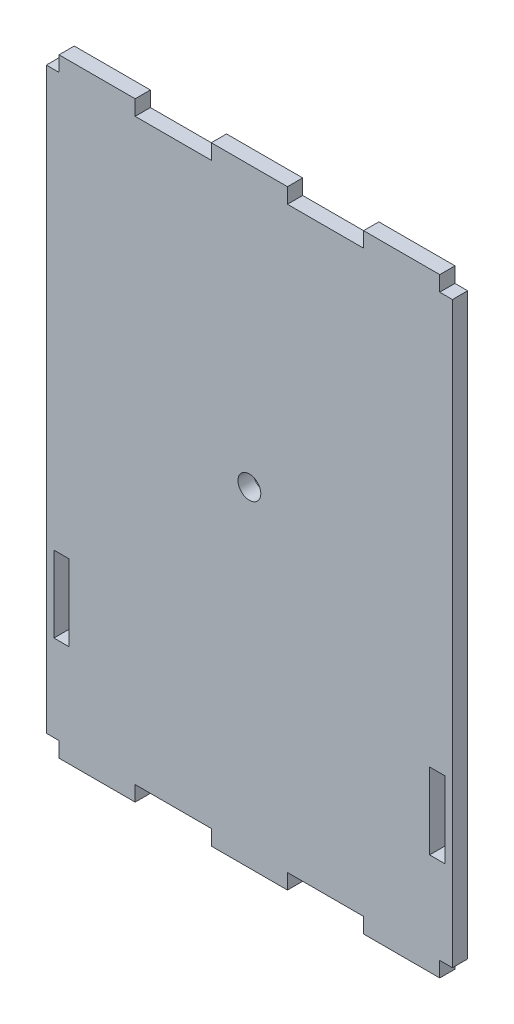
SolidWorks part; units mm, degrees
ref_plane "前视基准面" through (0, 0, 0) normal (0, 0, 1) x (1, 0, 0)
ref_plane "上视基准面" through (0, 0, 0) normal (0, 1, 0) x (1, 0, 0)
ref_plane "右视基准面" through (0, 0, 0) normal (1, 0, 0) x (0, 0, -1)
other "Configuration Table"
sketch "草图1" plane through (0, 0, 0) normal (0, 0, 1) x (1, 0, 0)
  line L0 (2.5, 3) -> (0, 3)
  line L2 (0, 3) -> (0, 117)
  line L4 (80, 3) -> (80, 117)
  line L5 (2.5, 0) -> (17.5, 0)
  line L6 (2.5, 0) -> (2.5, 3)
  line L8 (17.5, 0) -> (17.5, 3)
  line L9 (17.5, 3) -> (32.5, 3)
  line L10 (32.5, 0) -> (47.5, 0)
  line L11 (32.5, 0) -> (32.5, 3)
  line L13 (47.5, 0) -> (47.5, 3)
  line L14 (62.5, 0) -> (77.5, 0)
  line L15 (62.5, 0) -> (62.5, 3)
  line L17 (77.5, 0) -> (77.5, 3)
  line L18 (47.5, 3) -> (62.5, 3)
  line L19 (77.5, 3) -> (80, 3)
  line L20 (0, 120) -> (80, 0) construction
  line L21 (78.5, 20) -> (75.5, 20)
  line L22 (78.5, 20) -> (78.5, 35)
  line L23 (78.5, 35) -> (75.5, 35)
  line L24 (75.5, 20) -> (75.5, 35)
  line L25 (1.5, 20) -> (1.5, 35)
  line L26 (1.5, 35) -> (4.5, 35)
  line L27 (4.5, 20) -> (4.5, 35)
  line L28 (1.5, 20) -> (4.5, 20)
  line L29 (-20.6033, 60) -> (100.6033, 60) construction
  line L30 (77.5, 117) -> (80, 117)
  line L31 (77.5, 120) -> (77.5, 117)
  line L32 (77.5, 120) -> (62.5, 120)
  line L33 (62.5, 120) -> (62.5, 117)
  line L34 (47.5, 117) -> (62.5, 117)
  line L35 (47.5, 120) -> (47.5, 117)
  line L36 (2.5, 120) -> (17.5, 120)
  line L37 (32.5, 120) -> (32.5, 117)
  line L38 (17.5, 117) -> (32.5, 117)
  line L39 (2.5, 120) -> (2.5, 117)
  line L40 (17.5, 120) -> (17.5, 117)
  line L41 (32.5, 120) -> (47.5, 120)
  line L42 (2.5, 117) -> (0, 117)
  point P4 (80, 0)
  point P13 (17.5, 1.5)
  point P19 (62.5, 1.5)
  point P24 (0, 120)
  point P32 (40, 60)
  dimension "D3" = 15
  dimension "D4" = 3
  dimension "D5" = 2.5
  dimension "D6" = 15
  dimension "D7" = 15
  dimension "D8" = 3
  dimension "D9" = 15
  dimension "D10" = 1.5
  dimension "D11" = 20
  dimension "D12" = 20
  dimension "D13" = 1.5
  dimension "D14" = 3
extrude "凸台-拉伸1" add sketch "草图1" along normal blind 3
sketch "草图2" plane through (0, 0, 3) normal (0, 0, 1) x (1, 0, 0)
  line L0 (17.5, 120) -> (2.5, 120) construction
  line L1 (0, 117) -> (0, 3) construction
  line L2 (62.5, 0) -> (77.5, 0) construction
  line L3 (80, 3) -> (80, 117) construction
  line L4 (0, 120) -> (80, 0) construction
  line L5 (40, 128.2339) -> (40, -8.2339) construction
  line L6 (32.5, 0) -> (47.5, 0) construction
  circle A0 centre (40, 65) radius 2.25
  point P0 (0, 120)
  point P5 (80, 0)
  point P15 (40, 60)
  dimension "D1" = 4.5
  dimension "D2" = 65
extrude "切除-拉伸1" cut sketch "草图2" against normal blind 10
